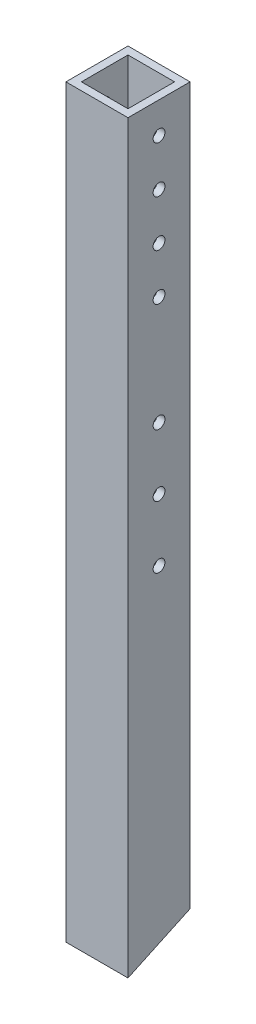
SolidWorks part; units mm, degrees
material "6061-T6 (SS)"
ref_plane "Front" through (0, 0, 0) normal (0, 0, 1) x (1, 0, 0)
ref_plane "Top" through (0, 0, 0) normal (0, 1, 0) x (1, 0, 0)
ref_plane "Right" through (0, 0, 0) normal (1, 0, 0) x (0, 0, -1)
sketch "Sketch1" plane through (0, 0, 0) normal (0, 1, 0) x (1, 0, 0)
  line L0 (-9.525, -9.525) -> (-9.525, 9.525)
  line L1 (-12.7, -12.7) -> (12.7, -12.7)
  line L2 (-12.7, -12.7) -> (-12.7, 12.7)
  line L3 (-12.7, 12.7) -> (12.7, 12.7)
  line L4 (12.7, -12.7) -> (12.7, 12.7)
  line L5 (-12.7, -12.7) -> (12.7, 12.7) construction
  line L6 (-12.7, 12.7) -> (12.7, -12.7) construction
  line L7 (-9.525, 9.525) -> (9.525, 9.525)
  line L8 (9.525, -9.525) -> (9.525, 9.525)
  line L9 (-9.525, -9.525) -> (9.525, -9.525)
  point P0 (0, 0)
  dimension "D1" = 25.4
  dimension "D2" = 3.175
extrude "Boss-Extrude1" add sketch "Sketch1" along normal blind 304.8
sketch "Sketch2" plane through (12.7, 0, 0) normal (1, 0, 0) x (0, 0, -1)
  line L0 (-12.7, 304.8) -> (12.7, 304.8) construction
  line L1 (0, 292.1) -> (0, 273.05) construction
  line L2 (0, 190.5) -> (0, 165.1) construction
  line L3 (-12.7, 0) -> (12.7, 11.8442)
  line L4 (12.7, 304.8) -> (12.7, 0) construction
  line L5 (12.7, 11.8442) -> (12.7, 0)
  line L6 (12.7, 0) -> (-12.7, 0)
  circle A0 centre (0, 292.1) radius 2.413
  circle A1 centre (0, 273.05) radius 2.413
  circle A2 centre (0, 254) radius 2.413
  circle A3 centre (0, 234.95) radius 2.413
  circle A4 centre (0, 190.5) radius 2.413
  circle A5 centre (0, 165.1) radius 2.413
  circle A6 centre (0, 139.7) radius 2.413
  dimension "D1" = 4.826
  dimension "D6" = 114.3
  dimension "D2" = 12.7
  dimension "D4" = 19.05
  dimension "D5" = 25
  dimension "D8" = 25.4
  dimension "D3" = 4
  dimension "D7" = 3
extrude "Cut-Extrude1" cut sketch "Sketch2" against normal blind 25.4
